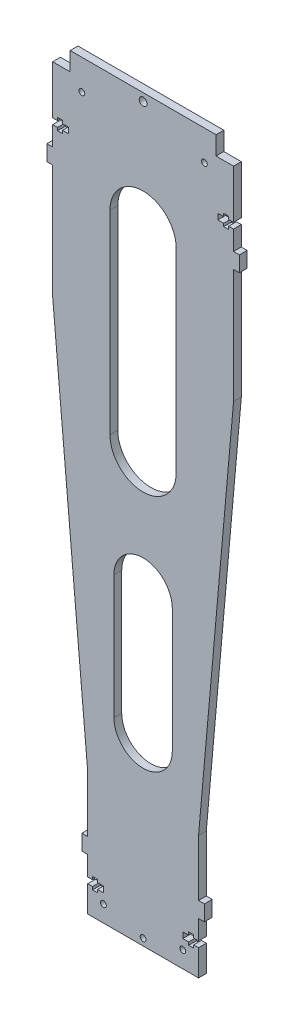
SolidWorks part; units mm, degrees
ref_plane "前视基准面" through (0, 0, 0) normal (0, 0, 1) x (1, 0, 0)
ref_plane "上视基准面" through (0, 0, 0) normal (0, 1, 0) x (1, 0, 0)
ref_plane "右视基准面" through (0, 0, 0) normal (1, 0, 0) x (0, 0, -1)
sketch "草图3" plane through (0, 0, 0) normal (0, 0, 1) x (1, 0, 0)
  line L2 (0, 10.5098) -> (0, 14.5098) construction
  line L10 (0, -1.9902) -> (0, 3.216) construction
  line L13 (-46.5, 5.0098) -> (-37.5, 5.0098)
  line L14 (-37.5, 5.0098) -> (-37.5, 14.5098)
  line L15 (-37.5, 14.5098) -> (37.5, 14.5098)
  line L20 (-44, -22.9902) -> (-44, -24.4902)
  line L21 (-44, -19.9902) -> (-44, -18.4902)
  line L22 (-46.5, -19.9902) -> (-44, -19.9902)
  line L23 (-44, -24.4902) -> (-41.4, -24.4902)
  line L24 (-41.4, -24.4902) -> (-41.4, -22.9902)
  line L25 (-41.4, -22.9902) -> (-38.4, -22.9902)
  line L26 (-38.4, -19.9902) -> (-38.4, -22.9902)
  line L27 (-41.4, -19.9902) -> (-38.4, -19.9902)
  line L28 (-41.4, -18.4902) -> (-41.4, -19.9902)
  line L29 (-44, -18.4902) -> (-41.4, -18.4902)
  line L30 (-44, -22.9902) -> (-46.5, -22.9902)
  line L34 (-46.5, -19.9902) -> (-46.5, -22.9902) construction
  line L36 (-46.5, -21.4902) -> (-44, -21.4902) construction
  line L37 (-46.5, -22.9902) -> (-46.5, -32.9902)
  line L38 (-46.5, -32.9902) -> (-49.5, -32.9902)
  line L39 (-49.5, -32.9902) -> (-49.5, -40.9902)
  line L40 (-49.5, -40.9902) -> (-46.5, -40.9902)
  line L64 (-46.5, -19.9902) -> (-46.5, 5.0098)
  line L67 (46.5, -21.4902) -> (44, -21.4902) construction
  line L68 (46.5, -19.9902) -> (46.5, -22.9902) construction
  line L70 (46.5, -19.9902) -> (46.5, 5.0098)
  line L72 (49.5, -40.9902) -> (46.5, -40.9902)
  line L73 (49.5, -32.9902) -> (49.5, -40.9902)
  line L74 (46.5, -32.9902) -> (49.5, -32.9902)
  line L75 (46.5, -22.9902) -> (46.5, -32.9902)
  line L76 (44, -22.9902) -> (46.5, -22.9902)
  line L77 (44, -18.4902) -> (41.4, -18.4902)
  line L78 (41.4, -18.4902) -> (41.4, -19.9902)
  line L79 (41.4, -19.9902) -> (38.4, -19.9902)
  line L80 (38.4, -19.9902) -> (38.4, -22.9902)
  line L81 (41.4, -22.9902) -> (38.4, -22.9902)
  line L82 (41.4, -24.4902) -> (41.4, -22.9902)
  line L83 (44, -24.4902) -> (41.4, -24.4902)
  line L84 (46.5, -19.9902) -> (44, -19.9902)
  line L85 (44, -19.9902) -> (44, -18.4902)
  line L86 (44, -22.9902) -> (44, -24.4902)
  line L87 (46.5, 5.0098) -> (37.5, 5.0098)
  line L88 (37.5, 5.0098) -> (37.5, 14.5098)
  line L119 (-46.5, -40.9902) -> (-46.5, -99.795)
  line L120 (46.5, -40.9902) -> (46.5, -99.795)
  line L123 (0, -361.9902) -> (0, -344.8152) construction
  line L128 (-28.5, -338.9902) -> (-31.5, -338.9902)
  line L129 (-31.5, -338.9902) -> (-31.5, -330.9902)
  line L130 (-31.5, -330.9902) -> (-28.5, -330.9902)
  line L152 (-28.5, -348.9902) -> (-28.5, -351.9902) construction
  line L153 (-28.5, -350.4902) -> (-26, -350.4902) construction
  line L154 (-26, -351.9902) -> (-26, -353.4902)
  line L155 (-26, -348.9902) -> (-26, -347.4902)
  line L156 (-28.5, -348.9902) -> (-26, -348.9902)
  line L157 (-26, -353.4902) -> (-23.4, -353.4902)
  line L158 (-23.4, -353.4902) -> (-23.4, -351.9902)
  line L159 (-23.4, -351.9902) -> (-20.4, -351.9902)
  line L160 (-20.4, -348.9902) -> (-20.4, -351.9902)
  line L161 (-23.4, -348.9902) -> (-20.4, -348.9902)
  line L162 (-23.4, -347.4902) -> (-23.4, -348.9902)
  line L163 (-26, -347.4902) -> (-23.4, -347.4902)
  line L164 (-26, -351.9902) -> (-28.5, -351.9902)
  line L165 (-28.5, -348.9902) -> (-28.5, -338.9902)
  line L166 (-28.5, -351.9902) -> (-28.5, -365.4902)
  line L167 (-28.5, -330.9902) -> (-28.5, -301.9902)
  line L169 (28.5, -351.9902) -> (28.5, -365.4902)
  line L170 (28.5, -350.4902) -> (26, -350.4902) construction
  line L171 (28.5, -348.9902) -> (28.5, -351.9902) construction
  line L172 (28.5, -330.9902) -> (28.5, -301.9902)
  line L173 (28.5, -348.9902) -> (28.5, -338.9902)
  line L174 (26, -351.9902) -> (28.5, -351.9902)
  line L175 (26, -347.4902) -> (23.4, -347.4902)
  line L176 (23.4, -347.4902) -> (23.4, -348.9902)
  line L177 (23.4, -348.9902) -> (20.4, -348.9902)
  line L178 (20.4, -348.9902) -> (20.4, -351.9902)
  line L179 (23.4, -351.9902) -> (20.4, -351.9902)
  line L180 (23.4, -353.4902) -> (23.4, -351.9902)
  line L181 (26, -353.4902) -> (23.4, -353.4902)
  line L182 (28.5, -348.9902) -> (26, -348.9902)
  line L183 (26, -348.9902) -> (26, -347.4902)
  line L184 (26, -351.9902) -> (26, -353.4902)
  line L185 (31.5, -330.9902) -> (28.5, -330.9902)
  line L186 (31.5, -338.9902) -> (31.5, -330.9902)
  line L187 (28.5, -338.9902) -> (31.5, -338.9902)
  line L189 (28.5, -365.4902) -> (-28.5, -365.4902)
  line L190 (-28.5, -301.9902) -> (-46.5, -99.795)
  line L191 (28.5, -301.9902) -> (46.5, -99.795)
  line L192 (0, -301.9902) -> (0, -176.9902) construction
  line L193 (0, -176.9902) -> (0, -15.6659) construction
  line L194 (0, -146.3281) -> (0, -46.3281) construction
  line L195 (-17.0232, -146.3281) -> (-17.0232, -46.3281)
  line L196 (17.0232, -146.3281) -> (17.0232, -46.3281)
  line L198 (0, -207.6524) -> (0, -271.3281) construction
  line L199 (-15, -207.6524) -> (-15, -271.3281)
  line L200 (15, -207.6524) -> (15, -271.3281)
  circle A0 centre (-31.5, -0.9902) radius 1.5
  circle A4 centre (0, 10.5098) radius 2
  circle A13 centre (-31.5, -0.9902) radius 3.5 construction
  circle A14 centre (31.5, -0.9902) radius 3.5 construction
  circle A15 centre (31.5, -0.9902) radius 1.5
  circle A16 centre (0, -361.9902) radius 1.5
  circle A17 centre (-20.4, -356.9902) radius 1.5
  circle A18 centre (20.4, -356.9902) radius 1.5
  arc A19 (-17.0232, -146.3281) -> (17.0232, -146.3281) centre (0, -146.3281) ccw
  arc A20 (17.0232, -46.3281) -> (-17.0232, -46.3281) centre (0, -46.3281) ccw
  arc A21 (-15, -207.6524) -> (15, -207.6524) centre (0, -207.6524) cw
  arc A22 (15, -271.3281) -> (-15, -271.3281) centre (0, -271.3281) cw
  point P107 (0, -96.3281)
  point P114 (0, 0)
  point P116 (0, -239.4902)
  dimension "D1" = 342.825
extrude "凸台-拉伸1" add sketch "草图3" along normal blind 4
